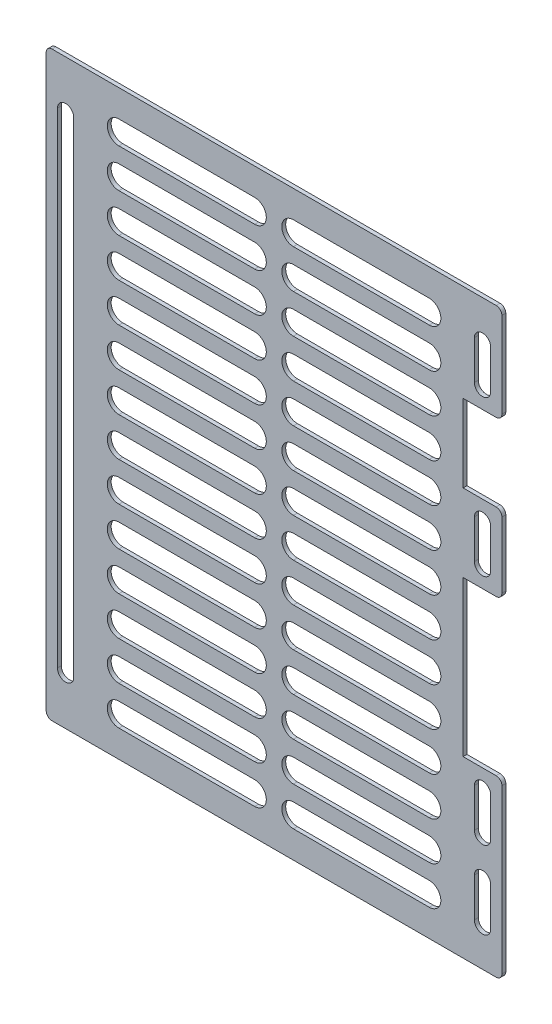
SolidWorks part; units mm, degrees
ref_plane "前视基准面" through (0, 0, 0) normal (0, 0, 1) x (1, 0, 0)
ref_plane "上视基准面" through (0, 0, 0) normal (0, 1, 0) x (1, 0, 0)
ref_plane "右视基准面" through (0, 0, 0) normal (1, 0, 0) x (0, 0, -1)
sketch "草图1" plane through (0, 0, 0) normal (0, 0, 1) x (1, 0, 0)
  line L1 (-117.5, 150) -> (117.5, 150)
  line L2 (-117.5, 150) -> (-117.5, -150)
  line L3 (-117.5, -150) -> (117.5, -150)
  line L4 (117.5, 150) -> (117.5, -150)
  line L5 (-117.5, 150) -> (117.5, -150) construction
  line L6 (-117.5, -150) -> (117.5, 150) construction
  point P0 (0, 0)
  dimension "D1" = 235
  dimension "D2" = 300
extrude "凸台-拉伸1" add sketch "草图1" along normal blind 2
sketch "草图4" plane through (0, 0, 2) normal (0, 0, 1) x (1, 0, 0)
  line L0 (-107.5, 125) -> (-107.5, -125) construction
  line L1 (-103.3, 125) -> (-103.3, -125)
  line L2 (-111.7, 125) -> (-111.7, -125)
  line L3 (-117.5, 150) -> (-117.5, -150) construction
  line L4 (117.5, 150) -> (-117.5, 150) construction
  line L5 (107.5, 130) -> (107.5, 110) construction
  line L6 (111.7, 130) -> (111.7, 110)
  line L7 (103.3, 130) -> (103.3, 110)
  line L8 (117.5, -150) -> (117.5, 150) construction
  line L9 (103.3, 90) -> (103.3, 70)
  line L10 (111.7, 90) -> (111.7, 70)
  line L11 (107.5, 90) -> (107.5, 70) construction
  line L12 (103.3, 50) -> (103.3, 30)
  line L13 (111.7, 50) -> (111.7, 30)
  line L14 (107.5, 50) -> (107.5, 30) construction
  line L15 (103.3, 10) -> (103.3, -10)
  line L16 (111.7, 10) -> (111.7, -10)
  line L17 (107.5, 10) -> (107.5, -10) construction
  line L18 (103.3, -30) -> (103.3, -50)
  line L19 (111.7, -30) -> (111.7, -50)
  line L20 (107.5, -30) -> (107.5, -50) construction
  line L21 (103.3, -70) -> (103.3, -90)
  line L22 (111.7, -70) -> (111.7, -90)
  line L23 (107.5, -70) -> (107.5, -90) construction
  line L24 (103.3, -110) -> (103.3, -130)
  line L25 (111.7, -110) -> (111.7, -130)
  line L26 (107.5, -110) -> (107.5, -130) construction
  line L27 (0, 150) -> (0, -150) construction
  line L28 (-117.5, -150) -> (117.5, -150) construction
  line L29 (-80, 130) -> (-10, 130) construction
  line L30 (-80, 136) -> (-10, 136)
  line L31 (-80, 124) -> (-10, 124)
  line L32 (-80, 104) -> (-10, 104)
  line L33 (-80, 116) -> (-10, 116)
  line L34 (-80, 110) -> (-10, 110) construction
  line L35 (-80, 84) -> (-10, 84)
  line L36 (-80, 96) -> (-10, 96)
  line L37 (-80, 90) -> (-10, 90) construction
  line L38 (-80, 64) -> (-10, 64)
  line L39 (-80, 76) -> (-10, 76)
  line L40 (-80, 70) -> (-10, 70) construction
  line L41 (-80, 44) -> (-10, 44)
  line L42 (-80, 56) -> (-10, 56)
  line L43 (-80, 50) -> (-10, 50) construction
  line L44 (-80, 24) -> (-10, 24)
  line L45 (-80, 36) -> (-10, 36)
  line L46 (-80, 30) -> (-10, 30) construction
  line L47 (-80, 4) -> (-10, 4)
  line L48 (-80, 16) -> (-10, 16)
  line L49 (-80, 10) -> (-10, 10) construction
  line L50 (-80, -16) -> (-10, -16)
  line L51 (-80, -4) -> (-10, -4)
  line L52 (-80, -10) -> (-10, -10) construction
  line L53 (-80, -36) -> (-10, -36)
  line L54 (-80, -24) -> (-10, -24)
  line L55 (-80, -30) -> (-10, -30) construction
  line L56 (-80, -56) -> (-10, -56)
  line L57 (-80, -44) -> (-10, -44)
  line L58 (-80, -50) -> (-10, -50) construction
  line L59 (-80, -76) -> (-10, -76)
  line L60 (-80, -64) -> (-10, -64)
  line L61 (-80, -70) -> (-10, -70) construction
  line L62 (-80, -96) -> (-10, -96)
  line L63 (-80, -84) -> (-10, -84)
  line L64 (-80, -90) -> (-10, -90) construction
  line L65 (-80, -116) -> (-10, -116)
  line L66 (-80, -104) -> (-10, -104)
  line L67 (-80, -110) -> (-10, -110) construction
  line L68 (-80, -136) -> (-10, -136)
  line L69 (-80, -124) -> (-10, -124)
  line L70 (-80, -130) -> (-10, -130) construction
  line L71 (80, -130) -> (10, -130) construction
  line L72 (80, -124) -> (10, -124)
  line L73 (80, -136) -> (10, -136)
  line L74 (80, -110) -> (10, -110) construction
  line L75 (80, -104) -> (10, -104)
  line L76 (80, -116) -> (10, -116)
  line L77 (80, -90) -> (10, -90) construction
  line L78 (80, -84) -> (10, -84)
  line L79 (80, -96) -> (10, -96)
  line L80 (80, -70) -> (10, -70) construction
  line L81 (80, -64) -> (10, -64)
  line L82 (80, -76) -> (10, -76)
  line L83 (80, -50) -> (10, -50) construction
  line L84 (80, -44) -> (10, -44)
  line L85 (80, -56) -> (10, -56)
  line L86 (80, -30) -> (10, -30) construction
  line L87 (80, -24) -> (10, -24)
  line L88 (80, -36) -> (10, -36)
  line L89 (80, -10) -> (10, -10) construction
  line L90 (80, -4) -> (10, -4)
  line L91 (80, -16) -> (10, -16)
  line L92 (80, 30) -> (10, 30) construction
  line L93 (80, 36) -> (10, 36)
  line L94 (80, 24) -> (10, 24)
  line L95 (80, 10) -> (10, 10) construction
  line L96 (80, 16) -> (10, 16)
  line L97 (80, 4) -> (10, 4)
  line L98 (80, 50) -> (10, 50) construction
  line L99 (80, 56) -> (10, 56)
  line L100 (80, 44) -> (10, 44)
  line L101 (80, 70) -> (10, 70) construction
  line L102 (80, 76) -> (10, 76)
  line L103 (80, 64) -> (10, 64)
  line L104 (80, 90) -> (10, 90) construction
  line L105 (80, 96) -> (10, 96)
  line L106 (80, 84) -> (10, 84)
  line L107 (80, 110) -> (10, 110) construction
  line L108 (80, 116) -> (10, 116)
  line L109 (80, 104) -> (10, 104)
  line L110 (80, 130) -> (10, 130) construction
  line L111 (80, 136) -> (10, 136)
  line L112 (80, 124) -> (10, 124)
  arc A0 (-103.3, 125) -> (-111.7, 125) centre (-107.5, 125) ccw
  arc A1 (-111.7, -125) -> (-103.3, -125) centre (-107.5, -125) ccw
  arc A2 (111.7, 130) -> (103.3, 130) centre (107.5, 130) ccw
  arc A3 (103.3, 110) -> (111.7, 110) centre (107.5, 110) ccw
  arc A4 (111.7, 90) -> (103.3, 90) centre (107.5, 90) ccw
  arc A5 (103.3, 70) -> (111.7, 70) centre (107.5, 70) ccw
  arc A6 (111.7, 50) -> (103.3, 50) centre (107.5, 50) ccw
  arc A7 (103.3, 30) -> (111.7, 30) centre (107.5, 30) ccw
  arc A8 (111.7, 10) -> (103.3, 10) centre (107.5, 10) ccw
  arc A9 (103.3, -10) -> (111.7, -10) centre (107.5, -10) ccw
  arc A10 (111.7, -30) -> (103.3, -30) centre (107.5, -30) ccw
  arc A11 (103.3, -50) -> (111.7, -50) centre (107.5, -50) ccw
  arc A12 (111.7, -70) -> (103.3, -70) centre (107.5, -70) ccw
  arc A13 (103.3, -90) -> (111.7, -90) centre (107.5, -90) ccw
  arc A14 (111.7, -110) -> (103.3, -110) centre (107.5, -110) ccw
  arc A15 (103.3, -130) -> (111.7, -130) centre (107.5, -130) ccw
  arc A16 (-80, 136) -> (-80, 124) centre (-80, 130) ccw
  arc A17 (-10, 124) -> (-10, 136) centre (-10, 130) ccw
  arc A18 (-80, 116) -> (-80, 104) centre (-80, 110) ccw
  arc A19 (-10, 104) -> (-10, 116) centre (-10, 110) ccw
  arc A20 (-80, 96) -> (-80, 84) centre (-80, 90) ccw
  arc A21 (-10, 84) -> (-10, 96) centre (-10, 90) ccw
  arc A22 (-80, 76) -> (-80, 64) centre (-80, 70) ccw
  arc A23 (-10, 64) -> (-10, 76) centre (-10, 70) ccw
  arc A24 (-80, 56) -> (-80, 44) centre (-80, 50) ccw
  arc A25 (-10, 44) -> (-10, 56) centre (-10, 50) ccw
  arc A26 (-80, 36) -> (-80, 24) centre (-80, 30) ccw
  arc A27 (-10, 24) -> (-10, 36) centre (-10, 30) ccw
  arc A28 (-80, 16) -> (-80, 4) centre (-80, 10) ccw
  arc A29 (-10, 4) -> (-10, 16) centre (-10, 10) ccw
  arc A30 (-80, -4) -> (-80, -16) centre (-80, -10) ccw
  arc A31 (-10, -16) -> (-10, -4) centre (-10, -10) ccw
  arc A32 (-80, -24) -> (-80, -36) centre (-80, -30) ccw
  arc A33 (-10, -36) -> (-10, -24) centre (-10, -30) ccw
  arc A34 (-80, -44) -> (-80, -56) centre (-80, -50) ccw
  arc A35 (-10, -56) -> (-10, -44) centre (-10, -50) ccw
  arc A36 (-80, -64) -> (-80, -76) centre (-80, -70) ccw
  arc A37 (-10, -76) -> (-10, -64) centre (-10, -70) ccw
  arc A38 (-80, -84) -> (-80, -96) centre (-80, -90) ccw
  arc A39 (-10, -96) -> (-10, -84) centre (-10, -90) ccw
  arc A40 (-80, -104) -> (-80, -116) centre (-80, -110) ccw
  arc A41 (-10, -116) -> (-10, -104) centre (-10, -110) ccw
  arc A42 (-80, -124) -> (-80, -136) centre (-80, -130) ccw
  arc A43 (-10, -136) -> (-10, -124) centre (-10, -130) ccw
  arc A44 (80, -124) -> (80, -136) centre (80, -130) cw
  arc A45 (10, -136) -> (10, -124) centre (10, -130) cw
  arc A46 (80, -104) -> (80, -116) centre (80, -110) cw
  arc A47 (10, -116) -> (10, -104) centre (10, -110) cw
  arc A48 (80, -84) -> (80, -96) centre (80, -90) cw
  arc A49 (10, -96) -> (10, -84) centre (10, -90) cw
  arc A50 (80, -64) -> (80, -76) centre (80, -70) cw
  arc A51 (10, -76) -> (10, -64) centre (10, -70) cw
  arc A52 (80, -44) -> (80, -56) centre (80, -50) cw
  arc A53 (10, -56) -> (10, -44) centre (10, -50) cw
  arc A54 (80, -24) -> (80, -36) centre (80, -30) cw
  arc A55 (10, -36) -> (10, -24) centre (10, -30) cw
  arc A56 (80, -4) -> (80, -16) centre (80, -10) cw
  arc A57 (10, -16) -> (10, -4) centre (10, -10) cw
  arc A58 (80, 36) -> (80, 24) centre (80, 30) cw
  arc A59 (10, 24) -> (10, 36) centre (10, 30) cw
  arc A60 (80, 16) -> (80, 4) centre (80, 10) cw
  arc A61 (10, 4) -> (10, 16) centre (10, 10) cw
  arc A62 (80, 56) -> (80, 44) centre (80, 50) cw
  arc A63 (10, 44) -> (10, 56) centre (10, 50) cw
  arc A64 (80, 76) -> (80, 64) centre (80, 70) cw
  arc A65 (10, 64) -> (10, 76) centre (10, 70) cw
  arc A66 (80, 96) -> (80, 84) centre (80, 90) cw
  arc A67 (10, 84) -> (10, 96) centre (10, 90) cw
  arc A68 (80, 116) -> (80, 104) centre (80, 110) cw
  arc A69 (10, 104) -> (10, 116) centre (10, 110) cw
  arc A70 (80, 136) -> (80, 124) centre (80, 130) cw
  arc A71 (10, 124) -> (10, 136) centre (10, 130) cw
  point P2 (-107.5, 0)
  point P13 (107.5, 120)
  point P23 (107.5, 80)
  point P30 (107.5, 40)
  point P37 (107.5, 0)
  point P44 (107.5, -40)
  point P51 (107.5, -80)
  point P58 (107.5, -120)
  point P68 (-45, 130)
  point P76 (-45, 110)
  point P83 (-45, 90)
  point P90 (-45, 70)
  point P97 (-45, 50)
  point P104 (-45, 30)
  point P111 (-45, 10)
  point P118 (-45, -10)
  point P125 (-45, -30)
  point P132 (-45, -50)
  point P139 (-45, -70)
  point P146 (-45, -90)
  point P153 (-45, -110)
  point P160 (-45, -130)
  point P166 (45, -130)
  point P173 (45, -110)
  point P180 (45, -90)
  point P187 (45, -70)
  point P194 (45, -50)
  point P201 (45, -30)
  point P208 (45, -10)
  point P215 (45, 30)
  point P222 (45, 10)
  point P229 (45, 50)
  point P236 (45, 70)
  point P243 (45, 90)
  point P250 (45, 110)
  point P257 (45, 130)
  dimension "D2" = 4.2
  dimension "D7" = 4.2
  dimension "D14" = 6
  dimension "D1" = 10
  dimension "D3" = 250
  dimension "D4" = 25
  dimension "D5" = 20
  dimension "D6" = 10
  dimension "D8" = 20
  dimension "D10" = 40
  dimension "D11" = 20
  dimension "D12" = 70
  dimension "D13" = 10
  dimension "D16" = 20
  dimension "D9" = 7
  dimension "D15" = 14
extrude "切除-拉伸1" cut sketch "草图4" against normal through all
sketch "草图5" plane through (0, 0, 2) normal (0, 0, 1) x (1, 0, 0)
  line L0 (117.5, -150) -> (117.5, 150) construction
  line L1 (97.5, 20) -> (117.5, 20)
  line L2 (97.5, 20) -> (97.5, -60)
  line L3 (97.5, -60) -> (117.5, -60)
  line L4 (117.5, 20) -> (117.5, -60)
  line L5 (97.5, 20) -> (117.5, -60) construction
  line L6 (97.5, -60) -> (117.5, 20) construction
  line L8 (97.5, 100) -> (117.5, 100)
  line L9 (97.5, 100) -> (97.5, 60)
  line L10 (97.5, 60) -> (117.5, 60)
  line L11 (117.5, 100) -> (117.5, 60)
  line L12 (97.5, 100) -> (117.5, 60) construction
  line L13 (97.5, 60) -> (117.5, 100) construction
  arc A0 (111.7, 50) -> (103.3, 50) centre (107.5, 50) ccw construction
  arc A1 (103.3, 110) -> (111.7, 110) centre (107.5, 110) ccw construction
  arc A2 (111.7, -70) -> (103.3, -70) centre (107.5, -70) ccw construction
  arc A3 (103.3, 30) -> (111.7, 30) centre (107.5, 30) ccw construction
  point P0 (107.5, -20)
  point P7 (107.5, 80)
  dimension "D3" = 10
  dimension "D4" = 10
  dimension "D5" = 10
  dimension "D1" = 20
  dimension "D2" = 20
  dimension "D6" = 10
extrude "切除-拉伸2" cut sketch "草图5" against normal through all
fillet "圆角1" radius 3 8 edges at (-117.5, 150, 1) (-117.5, -150, 1) (117.5, 100, 1) (117.5, 150, 1) (117.5, 60, 1) (117.5, 20, 1) (117.5, -60, 1) (117.5, -150, 1)
